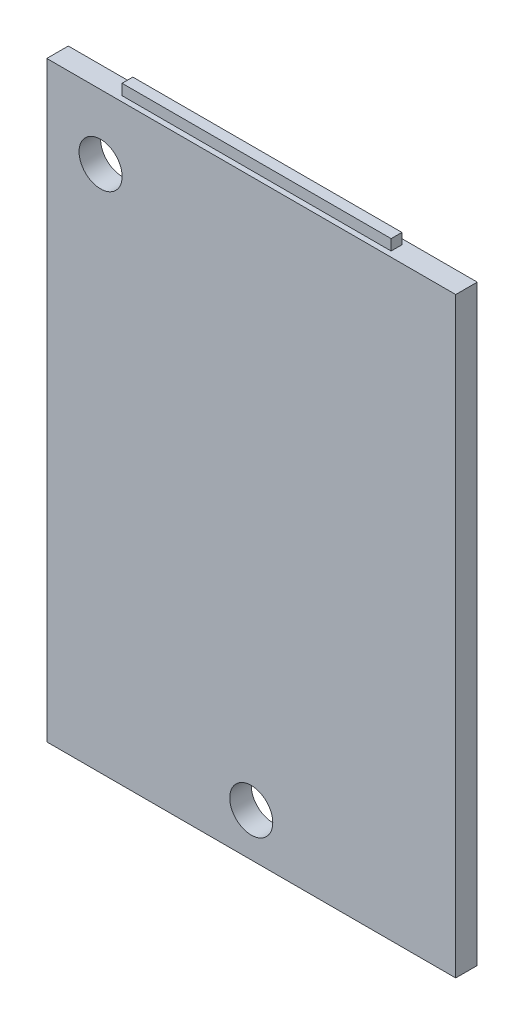
SolidWorks part; units mm, degrees
ref_plane "Front Plane" through (0, 0, 0) normal (0, 0, 1) x (1, 0, 0)
ref_plane "Top Plane" through (0, 0, 0) normal (0, 1, 0) x (1, 0, 0)
ref_plane "Right Plane" through (0, 0, 0) normal (1, 0, 0) x (0, 0, -1)
sketch "Sketch1" plane through (0, 0, 0) normal (0, 0, 1) x (1, 0, 0)
  line L1 (95, -137.5) -> (-95, -137.5)
  line L2 (95, -137.5) -> (95, 137.5)
  line L3 (95, 137.5) -> (-95, 137.5)
  line L4 (-95, -137.5) -> (-95, 137.5)
  line L5 (95, -137.5) -> (-95, 137.5) construction
  line L6 (95, 137.5) -> (-95, -137.5) construction
  point P0 (0, 0)
extrude "Boss-Extrude1" add sketch "Sketch1" along normal blind 10
sketch "Sketch2" plane through (0, 137.5, 0) normal (0, 1, 0) x (1, 0, 0)
  line L0 (0, 0) -> (0, -10) construction
  line L1 (95, 0) -> (-95, 0) construction
  line L2 (95, -10) -> (-95, -10) construction
  line L4 (62.5, -7.5) -> (-62.5, -7.5)
  line L5 (62.5, -7.5) -> (62.5, -2.5)
  line L6 (62.5, -2.5) -> (-62.5, -2.5)
  line L7 (-62.5, -7.5) -> (-62.5, -2.5)
  line L8 (62.5, -7.5) -> (-62.5, -2.5) construction
  line L9 (62.5, -2.5) -> (-62.5, -7.5) construction
  point P6 (0, -5)
extrude "Boss-Extrude2" add sketch "Sketch2" along normal blind 5
sketch "Sketch3" plane through (0, 0, 10) normal (0, 0, 1) x (1, 0, 0)
  line L0 (0, -137.5) -> (0, -117.5) construction
  line L1 (-95, -137.5) -> (95, -137.5) construction
  line L2 (-95, 137.5) -> (-70, 137.5) construction
  line L3 (95, 137.5) -> (-95, 137.5) construction
  line L4 (-70, 137.5) -> (-70, 107.5) construction
  circle A0 centre (0, -117.5) radius 10
  circle A1 centre (-70, 107.5) radius 10
extrude "Cut-Extrude1" cut sketch "Sketch3" against normal blind 16
